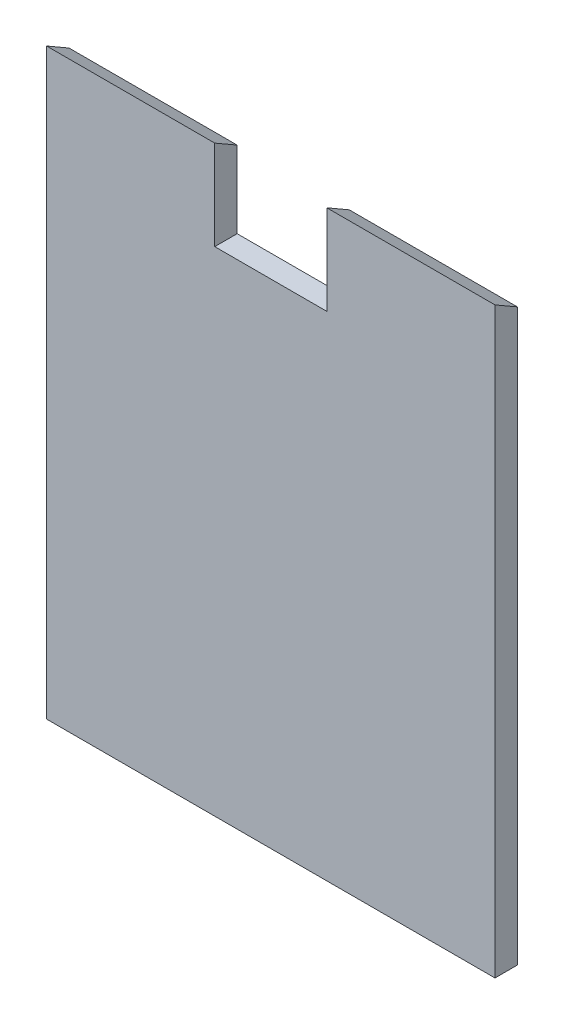
SolidWorks part; units mm, degrees
ref_plane "Front Plane" through (0, 0, 0) normal (0, 0, 1) x (1, 0, 0)
ref_plane "Top Plane" through (0, 0, 0) normal (0, 1, 0) x (1, 0, 0)
ref_plane "Right Plane" through (0, 0, 0) normal (1, 0, 0) x (0, 0, -1)
sketch "Sketch1" plane through (0, 0, 0) normal (0, 0, 1) x (1, 0, 0)
  line L0 (0, -262.711) -> (0, 262.711) construction
  line L1 (127, -165.1) -> (-127, -165.1)
  line L2 (127, -165.1) -> (127, 165.1)
  line L3 (127, 165.1) -> (31.75, 165.1)
  line L4 (-127, -165.1) -> (-127, 165.1)
  line L5 (127, -165.1) -> (-127, 165.1) construction
  line L6 (127, 165.1) -> (-127, -165.1) construction
  line L7 (-31.75, 114.3) -> (31.75, 114.3)
  line L8 (-31.75, 114.3) -> (-31.75, 165.1)
  line L9 (31.75, 114.3) -> (31.75, 165.1)
  line L10 (-31.75, 165.1) -> (-127, 165.1)
  point P0 (0, 0)
  point P9 (0, 0)
  point P12 (0, 114.3)
  dimension "D1" = 330.2
  dimension "D2" = 254
  dimension "D3" = 63.5
  dimension "D4" = 50.8
extrude "Boss-Extrude1" add sketch "Sketch1" along normal mid plane 12.7
sketch "Sketch2" plane through (0, 0, 0) normal (1, 0, 0) x (0, 0, -1)
  line L0 (0, -209.8682) -> (0, 209.8682) construction
  line L1 (-6.35, 165.1) -> (6.35, 165.1)
  line L2 (-6.35, 165.1) -> (6.35, 165.1) construction
  line L3 (6.35, -165.1) -> (6.35, 165.1) construction
  line L4 (6.35, 165.1) -> (6.35, 157.7677)
  line L5 (-6.35, 165.1) -> (6.35, 157.7677)
  point P4 (0, 0)
  dimension "D1" = 30
extrude "Cut-Extrude1" cut sketch "Sketch2" against normal mid plane 254
